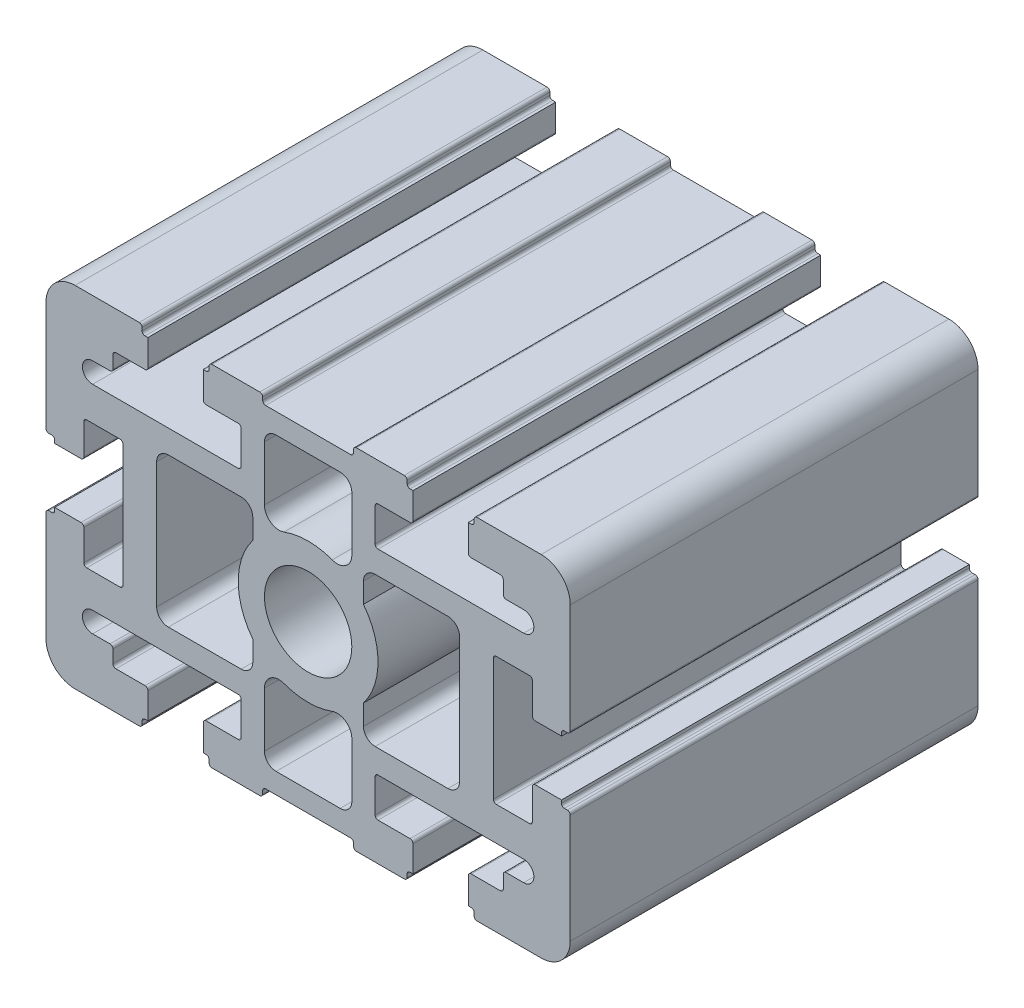
SolidWorks part; units mm, degrees
material "6061 Alaşım"
ref_plane "Ön Düzlem" through (0, 0, 0) normal (0, 0, 1) x (1, 0, 0)
ref_plane "Üst Düzlem" through (0, 0, 0) normal (0, 1, 0) x (1, 0, 0)
ref_plane "Sağ Düzlem" through (0, 0, 0) normal (1, 0, 0) x (0, 0, -1)
sketch "Çizim1" plane through (0, 0, 0) normal (0, 0, 1) x (1, 0, 0)
  line L1 (45, -30) -> (-45, -30) construction
  line L2 (45, -30) -> (45, 30) construction
  line L3 (45, 30) -> (-45, 30) construction
  line L4 (-45, -30) -> (-45, 30) construction
  line L5 (45, -30) -> (-45, 30) construction
  line L6 (45, 30) -> (-45, -30) construction
  point P0 (0, 0)
  dimension "D1" = 90
  dimension "D2" = 60
sketch "Çizim3" plane through (0, 0, 0) normal (0, 0, 1) x (1, 0, 0)
  line L0 (0, 0) -> (-45, 0) construction
  line L1 (-45, -30) -> (-45, 30) construction
  line L2 (-39, 4.75) -> (-43.5, 4.75)
  line L3 (-24, 12.8) -> (-11.5, 12.8)
  line L4 (-26, 10.8) -> (-26, 0)
  line L5 (-26, 0) -> (-9.5, 0) construction
  line L6 (-9.5, 10.8) -> (-9.5, 0) construction
  line L7 (-38, 11) -> (-32.3, 11)
  line L8 (-38.5, 11) -> (-38.5, 0) construction
  line L9 (-38.5, 0) -> (-31.8, 0)
  line L10 (-31.8, 10.5) -> (-31.8, 0)
  line L15 (-43.5, 4.75) -> (-43.5, 5.25)
  line L16 (-44, 5.75) -> (-44.5, 5.75)
  line L17 (-45, 6.25) -> (-45, 25)
  line L18 (-40, 30) -> (-29, 30)
  line L19 (45, 30) -> (-45, 30) construction
  line L20 (-28.5, 29.5) -> (-28.5, 29)
  line L21 (-28, 28.5) -> (-27.5, 28.5)
  line L22 (-27.5, 28.5) -> (-27.5, 24)
  line L23 (-28, 23.5) -> (-33, 23.5)
  line L24 (-33.5, 23) -> (-33.5, 20.8)
  line L25 (-34, 20.3) -> (-37, 20.3)
  line L26 (-37, 16.8) -> (-12, 16.8)
  line L27 (-11.5, 17.3) -> (-11.5, 23)
  line L28 (-12, 23.5) -> (-17.5, 23.5)
  line L29 (-18, 24) -> (-18, 28.5)
  line L30 (-18, 28.5) -> (-17.5, 28.5)
  line L31 (-17, 29) -> (-17, 29.5)
  line L32 (-16.5, 30) -> (-8.3, 30)
  line L33 (-7.8, 29.5) -> (-7.8, 29)
  line L34 (-7.3, 28.5) -> (0, 28.5)
  line L35 (0, 0) -> (0, 30) construction
  line L36 (0, 25) -> (-5.5, 25)
  line L37 (-7.5, 23) -> (-7.5, 13.6107)
  line L38 (-9.5, 10.8) -> (-9.5, 7.3314)
  line L39 (-38.5, 5.25) -> (-38.5, 10.5)
  line L40 (-31.8, 0) -> (-26, 0)
  line L41 (0, 28.5) -> (0, 25)
  line L42 (-31.8, 0) -> (-26, 0)
  line L43 (-12, 0) -> (-7.5, 0)
  line L44 (0, 12) -> (0, 7.5)
  line L45 (-31.8, 0) -> (-26, 0)
  line L46 (0, 0) -> (0, 12)
  line L47 (-12, 0) -> (0, 0)
  line L48 (-12, 0) -> (-26, 0)
  line L49 (0, 30) -> (0, 0)
  line L50 (-45, 0) -> (-45, 30)
  line L51 (-45, 30) -> (0, 30)
  circle A0 centre (0, 0) radius 7.5
  circle A1 centre (0, 0) radius 12 construction
  arc A2 (-37, 20.3) -> (-37, 16.8) centre (-37, 18.55) ccw
  arc A3 (0, 12) -> (-4.1379, 11.264) centre (0, 0) ccw
  arc A4 (-4.1379, 11.264) -> (-7.5, 13.6107) centre (-5, 13.6107) cw
  arc A5 (-24, 12.8) -> (-26, 10.8) centre (-24, 10.8) ccw
  arc A6 (-11.5, 12.8) -> (-9.5, 10.8) centre (-11.5, 10.8) cw
  arc A7 (-5.5, 25) -> (-7.5, 23) centre (-5.5, 23) ccw
  arc A8 (-45, 25) -> (-40, 30) centre (-40, 25) cw
  arc A9 (-8.3, 30) -> (-7.8, 29.5) centre (-8.3, 29.5) cw
  arc A10 (-7.8, 29) -> (-7.3, 28.5) centre (-7.3, 29) ccw
  arc A11 (-33.5, 20.8) -> (-34, 20.3) centre (-34, 20.8) cw
  arc A12 (-12, 16.8) -> (-11.5, 17.3) centre (-12, 17.3) ccw
  arc A13 (-27.5, 24) -> (-28, 23.5) centre (-28, 24) cw
  arc A14 (-17.5, 23.5) -> (-18, 24) centre (-17.5, 24) cw
  arc A15 (-11.5, 23) -> (-12, 23.5) centre (-12, 23) ccw
  arc A16 (-17, 29.5) -> (-16.5, 30) centre (-16.5, 29.5) cw
  arc A17 (-17.5, 28.5) -> (-17, 29) centre (-17.5, 29) ccw
  arc A18 (-29, 30) -> (-28.5, 29.5) centre (-29, 29.5) cw
  arc A19 (-28.5, 29) -> (-28, 28.5) centre (-28, 29) ccw
  arc A20 (-33, 23.5) -> (-33.5, 23) centre (-33, 23) ccw
  arc A21 (-32.3, 11) -> (-31.8, 10.5) centre (-32.3, 10.5) cw
  arc A22 (-38, 11) -> (-38.5, 10.5) centre (-38, 10.5) ccw
  arc A23 (-39, 4.75) -> (-38.5, 5.25) centre (-39, 5.25) ccw
  arc A24 (-43.5, 5.25) -> (-44, 5.75) centre (-44, 5.25) ccw
  arc A25 (-44.5, 5.75) -> (-45, 6.25) centre (-44.5, 6.25) cw
  arc A26 (-12, 0) -> (-9.5, 7.3314) centre (0, 0) cw
  point P58 (-45, 30)
  point P61 (-7.8, 30)
  point P66 (-33.5, 20.3)
  point P71 (-27.5, 23.5)
  point P78 (-17, 30)
  point P81 (-17, 28.5)
  point P84 (-28.5, 30)
  point P87 (-28.5, 28.5)
  point P90 (-33.5, 23.5)
  point P98 (-38.5, 4.75)
  point P101 (-43.5, 5.75)
  point P104 (-45, 5.75)
  dimension "D25" = 15
  dimension "D26" = 24
  dimension "D24" = 2.5
  dimension "D27" = 2
  dimension "D28" = 5
  dimension "D29" = 0.5
  dimension "D1" = 6.5
  dimension "D2" = 5
  dimension "D3" = 1
  dimension "D4" = 4.75
  dimension "D5" = 6.7
  dimension "D6" = 5.8
  dimension "D7" = 11
  dimension "D8" = 5.8
  dimension "D9" = 4
  dimension "D10" = 9.5
  dimension "D11" = 6.5
  dimension "D12" = 5
  dimension "D13" = 1
  dimension "D14" = 17.5
  dimension "D15" = 9.5
  dimension "D16" = 6
  dimension "D17" = 3.5
  dimension "D18" = 3.5
  dimension "D19" = 7.5
  dimension "D20" = 1.5
  dimension "D21" = 3.5
  dimension "D22" = 9.2
  dimension "D23" = 4
extrude "Yükseklik-Ekstrüzyon1" add sketch "Çizim3" along normal blind 70 contours A26 L43 A0 L44 A3 A4 L37 A7 L36 L41 L34 A10 L33 A9 L32 A16 L31 A17 L30 L29 A14 L28 A15 L27 A12 L26 A2 L25 A11 L24 A20 L23 A13 L22 L21 A19 L20 A18 L18 A8 L17 A25 L16 A24 L15 L2 A23 L39 A22 L7 A21
mirror "Aynalama1" about plane through (0, 0, 70) normal (1, 0, 0) of bodies 101
mirror "Aynalama2" about plane through (0, 0, 70) normal (0, 1, 0) of bodies 102
